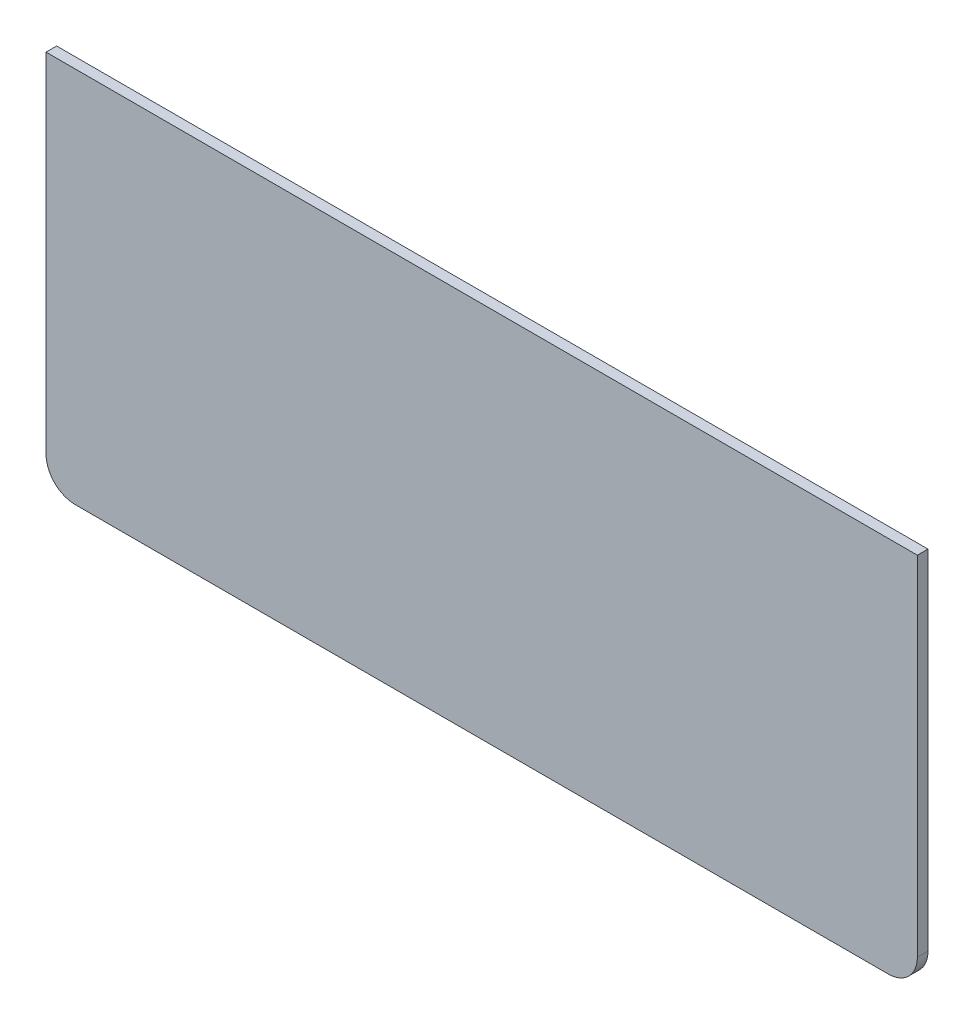
SolidWorks part; units mm, degrees
material "5052-H32"
ref_plane "Front Plane" through (0, 0, 0) normal (0, 0, 1) x (1, 0, 0)
ref_plane "Top Plane" through (0, 0, 0) normal (0, 1, 0) x (1, 0, 0)
ref_plane "Right Plane" through (0, 0, 0) normal (1, 0, 0) x (0, 0, -1)
sketch "Sketch2" plane through (0, 0, 0) normal (0, 0, 1) x (1, 0, 0)
  line L0 (-53.5866, 40.5355) -> (207.7634, 40.5355)
  line L1 (207.7634, 40.5355) -> (207.7634, -72.6395)
  line L2 (207.7634, -72.6395) -> (-53.5866, -72.6395)
  line L3 (-53.5866, -72.6395) -> (-53.5866, 40.5355)
  dimension "D1" = 113.175
  dimension "D2" = 261.35
extrude "Boss-Extrude1" add sketch "Sketch2" along normal blind 3.175
fillet "Fillet1" radius 8.7312 2 edges at (-53.5866, -72.6395, 1.5875) (207.7634, -72.6395, 1.5875)
equation "\"L\"= 420mm"
equation "\"W\"= 255mm"
equation "\"H\"= 110mm"
equation "\"Compartment Width\"= 80"
equation "\"T\"= 4.7625 * 2 / 3mm"
equation "\"Inside Fillet Radius\"= 5.55625mm"
equation "\"D1@Fillet1\"=\"Inside Fillet Radius\"+\"T\""
equation "\"D1@Sketch2\"=\"T\"+\"H\""
equation "\"D2@Sketch2\"=2*\"T\"+\"W\""
equation "\"D1@Boss-Extrude1\"=\"T\""
equation "\"Offset\"= 18mm"
equation "\"Hole\"=25mm"
equation "\"Wheel to Wall\"= 43"
